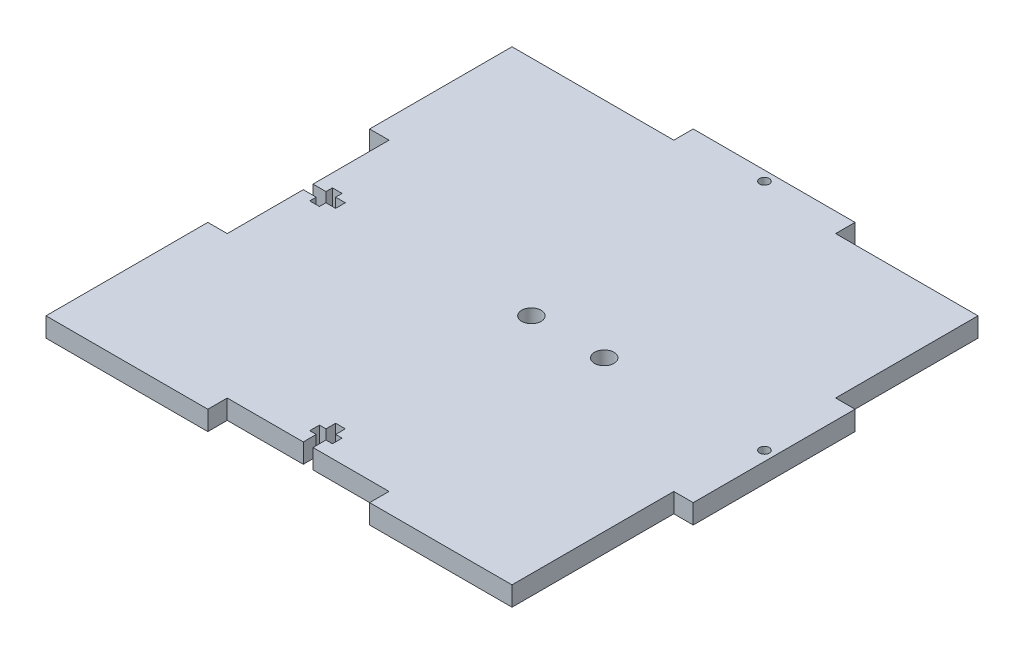
SolidWorks part; units mm, degrees
material "Acrylic (Medium-high impact)"
ref_plane "Front Plane" through (0, 0, 0) normal (0, 0, 1) x (1, 0, 0)
ref_plane "Top Plane" through (0, 0, 0) normal (0, 1, 0) x (1, 0, 0)
ref_plane "Right Plane" through (0, 0, 0) normal (1, 0, 0) x (0, 0, -1)
sketch "Sketch1" plane through (0, 0, 0) normal (0, 1, 0) x (1, 0, 0)
  line L0 (-72, 28) -> (-66, 28)
  line L1 (-72, -72) -> (72, -72)
  line L2 (-72, -72) -> (-72, 72)
  line L3 (-72, 72) -> (72, 72)
  line L4 (72, -72) -> (72, 72)
  line L5 (-72, -72) -> (72, 72) construction
  line L6 (-72, 72) -> (72, -72) construction
  line L7 (-66, 28) -> (-66, -22)
  line L8 (28, -72) -> (28, -66)
  line L9 (-22, 72) -> (-22, 78)
  line L10 (-22, 78) -> (28, 78)
  line L11 (28, 72) -> (28, 78)
  line L12 (72, 28) -> (78, 28)
  line L13 (78, 28) -> (78, -22)
  line L14 (-22, -72) -> (-22, -66)
  line L15 (-22, -66) -> (28, -66)
  line L16 (3, 78) -> (3, -72) construction
  line L17 (-72, 3) -> (78, 3) construction
  line L18 (72, -22) -> (78, -22)
  line L19 (-72, -22) -> (-66, -22)
  line L20 (75, 28) -> (75, -22) construction
  line L21 (4.5, -66) -> (4.5, -62)
  line L22 (4.5, -62) -> (6.5, -62)
  line L23 (6.5, -62) -> (6.5, -59)
  line L24 (6.5, -59) -> (4.5, -59)
  line L25 (4.5, -59) -> (4.5, -56)
  line L26 (4.5, -56) -> (1.5, -56)
  line L27 (1.5, -66) -> (1.5, -62)
  line L28 (1.5, -62) -> (-0.5, -62)
  line L29 (-0.5, -59) -> (1.5, -59)
  line L30 (-0.5, -62) -> (-0.5, -59)
  line L31 (1.5, -59) -> (1.5, -56)
  line L32 (-59, 4.5) -> (-56, 4.5)
  line L33 (-62, 4.5) -> (-62, 6.5)
  line L34 (-59, 6.5) -> (-59, 4.5)
  line L35 (-62, 6.5) -> (-59, 6.5)
  line L36 (-66, 4.5) -> (-62, 4.5)
  line L37 (-66, 1.5) -> (-62, 1.5)
  line L38 (-62, 1.5) -> (-62, -0.5)
  line L39 (-62, -0.5) -> (-59, -0.5)
  line L40 (-59, -0.5) -> (-59, 1.5)
  line L41 (-59, 1.5) -> (-56, 1.5)
  line L42 (-56, 4.5) -> (-56, 1.5)
  circle A0 centre (75, 3) radius 1.5
  circle A1 centre (3, 75) radius 1.5
  circle A2 centre (3, 3) radius 3
  circle A3 centre (25.5, 3) radius 3
  point P0 (0, 0)
  point P22 (3, 3)
  point P27 (3, 3)
  point P40 (3, -66)
  point P45 (-66, 3)
  point P49 (3, -56)
  dimension "D4" = 3
  dimension "D9" = 6
  dimension "D1" = 144
  dimension "D2" = 25
  dimension "D3" = 6
  dimension "D5" = 4
  dimension "D6" = 2
  dimension "D7" = 3
  dimension "D8" = 1.5
  dimension "D10" = 2
extrude "Boss-Extrude1" add sketch "Sketch1" along normal blind 6 contours L19 L2 L1 L14 L15 L8 L4 L3 L0 L7 | L3 L11 L10 L9 | L4 L18 L13 L12
